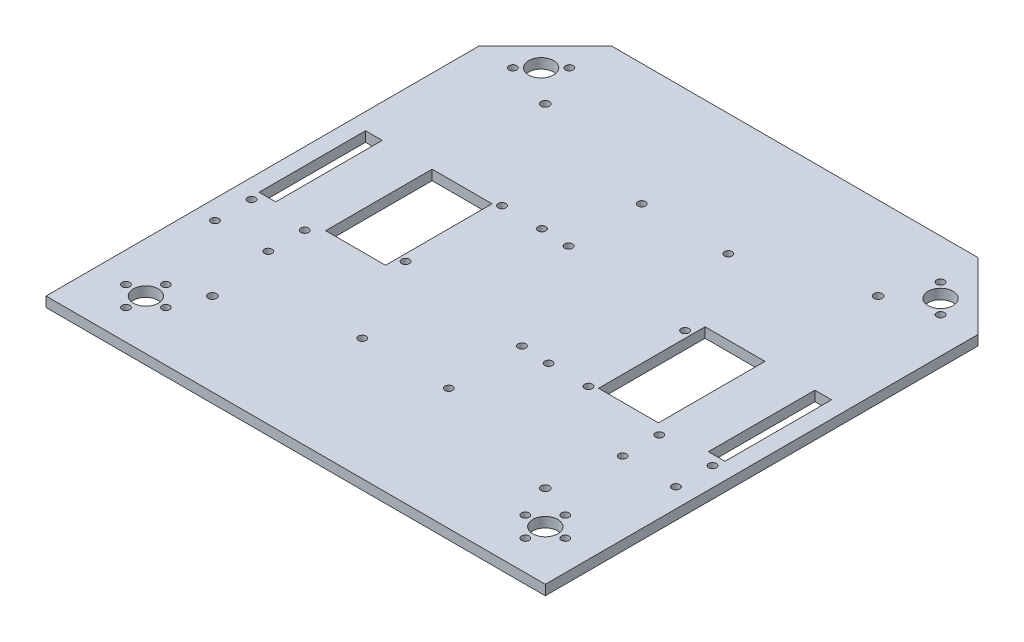
SolidWorks part; units mm, degrees
ref_plane "Plan de face" through (0, 0, 0) normal (0, 0, 1) x (1, 0, 0)
ref_plane "Plan de dessus" through (0, 0, 0) normal (0, 1, 0) x (1, 0, 0)
ref_plane "Plan de droite" through (0, 0, 0) normal (1, 0, 0) x (0, 0, -1)
sketch "Esquisse1" plane through (0, 0, 0) normal (0, 1, 0) x (1, 0, 0)
  line L0 (-150, 0) -> (-150, 260)
  line L2 (150, 0) -> (150, 260)
  line L3 (-150, 260) -> (-110, 260) construction
  line L4 (-110, 260) -> (-110, 300) construction
  line L5 (150, 260) -> (110, 260) construction
  line L6 (110, 260) -> (110, 300) construction
  line L8 (-150, 260) -> (-110, 300)
  line L9 (-110, 300) -> (110, 300)
  line L10 (0, 0) -> (0, 300) construction
  line L11 (110, 300) -> (150, 260)
  line L12 (-150, 0) -> (-120, 0) construction
  line L13 (-120, 18) -> (-120, 0) construction
  line L14 (150, 0) -> (120, 0) construction
  line L15 (120, 18) -> (120, 0) construction
  line L17 (-150, 260) -> (-120, 260) construction
  line L18 (-120, 260) -> (-120, 267.5) construction
  line L19 (150, 260) -> (120, 260) construction
  line L20 (120, 260) -> (120, 267.5) construction
  line L21 (-120, 267.5) -> (-111.5147, 275.9853) construction
  line L22 (-120, 267.5) -> (-128.4853, 259.0147) construction
  line L23 (120, 267.5) -> (128.4853, 259.0147) construction
  line L24 (120, 267.5) -> (111.5147, 275.9853) construction
  line L25 (-150, 0) -> (150, 0) construction
  line L26 (120, 30) -> (120, 18) construction
  line L27 (120, 30) -> (120, 42) construction
  line L28 (-150, 0) -> (150, 0)
  line L29 (-120, 18) -> (-120, 30) construction
  line L30 (-120, 30) -> (-120, 42) construction
  line L32 (150, 150) -> (-150, 150) construction
  line L33 (-120, 30) -> (-108, 30) construction
  line L34 (-120, 30) -> (-132, 30) construction
  line L35 (120, 30) -> (132, 30) construction
  line L36 (120, 30) -> (108, 30) construction
  circle A2 centre (-120, 30) radius 7.5
  circle A4 centre (-120, 267.5) radius 7.5
  circle A5 centre (120, 267.5) radius 7.5
  circle A6 centre (-111.5147, 275.9853) radius 2.3
  circle A7 centre (-128.4853, 259.0147) radius 2.3
  circle A8 centre (111.5147, 275.9853) radius 2.3
  circle A9 centre (128.4853, 259.0147) radius 2.3
  circle A10 centre (120, 30) radius 7.5
  circle A11 centre (120, 42) radius 2.3
  circle A13 centre (-120, 42) radius 2.3
  circle A14 centre (-120, 18) radius 2.3
  circle A16 centre (-132, 30) radius 2.3
  circle A17 centre (-108, 30) radius 2.3
  circle A18 centre (108, 30) radius 2.3
  circle A19 centre (132, 30) radius 2.3
  circle A20 centre (120, 18) radius 2.3
extrude "Boss.-Extru.1" add sketch "Esquisse1" along normal blind 6
sketch "Esquisse7" plane through (0, 6, 0) normal (0, 1, 0) x (1, 0, 0)
  line L0 (0, 150) -> (-130, 150) construction
  line L1 (0, 0) -> (0, 300) construction
  line L2 (150, 150) -> (-150, 150) construction
  line L3 (-130, 150) -> (-130, 182)
  line L4 (-130, 182) -> (-140, 182)
  line L5 (-140, 182) -> (-140, 118)
  line L6 (-140, 118) -> (-130, 118)
  line L7 (-130, 118) -> (-130, 150)
extrude "Enlèv. mat.-Extru.9" cut sketch "Esquisse7" against normal blind 10.5
sketch "Esquisse6" plane through (0, 6, 0) normal (0, 1, 0) x (1, 0, 0)
  line L0 (-142.5, 116) -> (-134.5, 116) construction
  line L2 (-142.5, 116) -> (-142.5, 150) construction
  line L3 (-142.5, 116) -> (-142.5, 108) construction
  line L11 (-142.5, 108) -> (-134.5, 108) construction
  line L12 (-134.5, 108) -> (-134.5, 116) construction
  line L14 (-142.5, 150) -> (-150, 150) construction
  line L15 (-142.5, 116) -> (-102.5, 116) construction
  line L16 (-102.5, 116) -> (-102.5, 108) construction
  line L17 (-102.5, 108) -> (-110.5, 108) construction
  line L18 (-110.5, 108) -> (-110.5, 116) construction
  line L19 (-110.5, 116) -> (-134.5, 116) construction
  line L20 (-134.5, 116) -> (-134.5, 86) construction
  line L21 (-134.5, 86) -> (-142.5, 86) construction
  line L22 (-142.5, 86) -> (-142.5, 94) construction
  line L23 (-142.5, 94) -> (-134.5, 94) construction
  line L24 (-134.5, 94) -> (-134.5, 86) construction
  line L25 (-134.5, 86) -> (-110.5, 86) construction
  line L26 (-110.5, 86) -> (-110.5, 94) construction
  line L27 (-110.5, 94) -> (-102.5, 94) construction
  line L28 (-102.5, 94) -> (-102.5, 86) construction
  line L29 (-102.5, 86) -> (-110.5, 86) construction
  line L30 (-102.5, 94) -> (-110.5, 86) construction
  line L31 (-110.5, 94) -> (-102.5, 86) construction
  line L32 (-142.5, 94) -> (-134.5, 86) construction
  line L33 (-142.5, 86) -> (-134.5, 94) construction
  line L34 (-142.5, 116) -> (-134.5, 108) construction
  line L35 (-142.5, 108) -> (-134.5, 116) construction
  line L71 (-110.5, 116) -> (-102.5, 108) construction
  line L72 (-110.5, 108) -> (-102.5, 116) construction
  line L73 (-110.5, 116) -> (-110.5, 86) construction
  circle A20 centre (-138.5, 90) radius 2.3
  circle A21 centre (-138.5, 112) radius 2.3
  circle A22 centre (-106.5, 112) radius 2.3
  circle A23 centre (-106.5, 90) radius 2.3
  dimension "D1" = 7.5
  dimension "D2" = 34
sketch "Esquisse4" plane through (0, 6, 0) normal (0, 1, 0) x (1, 0, 0)
  line L0 (-150, 150) -> (-100, 150) construction
  line L8 (150, 150) -> (-150, 150) construction
  line L14 (-100, 150) -> (-100, 182)
  line L15 (-100, 250) -> (-100, 50) construction
  line L16 (-100, 150) -> (-100, 118)
  line L17 (-100, 118) -> (-64, 118)
  line L18 (-64, 118) -> (-64, 182)
  line L19 (-64, 182) -> (-100, 182)
sketch "Esquisse9" plane through (0, 6, 0) normal (0, 1, 0) x (1, 0, 0)
  line L0 (-150, 0) -> (150, 0) construction
  line L1 (150, 0) -> (150, 300) construction
  line L2 (150, 300) -> (-150, 300) construction
  line L3 (-150, 300) -> (-150, 0) construction
  line L5 (-150, 0) -> (-150, 300) construction
  line L6 (150, 0) -> (0, 0) construction
  line L7 (0, 0) -> (0, 50) construction
  line L8 (0, 0) -> (0, 300) construction
  line L9 (0, 50) -> (100, 50) construction
  line L10 (100, 50) -> (100, 250) construction
  line L11 (100, 250) -> (-100, 250) construction
  line L12 (-100, 250) -> (-100, 50) construction
  line L13 (-100, 50) -> (0, 50) construction
  line L18 (100, 250) -> (94.3431, 244.3431) construction
  line L21 (-150, 0) -> (150, 300) construction
  circle A0 centre (-100, 50) radius 2.5
  circle A1 centre (100, 50) radius 2.5
  circle A2 centre (100, 250) radius 2.5
  circle A3 centre (-100, 250) radius 2.5
extrude "Enlèv. mat.-Extru.10" cut sketch "Esquisse6" against normal blind 50
extrude "Enlèv. mat.-Extru.11" cut sketch "Esquisse4" against normal blind 50
sketch "Esquisse3" plane through (0, 6, 0) normal (0, 1, 0) x (1, 0, 0)
  line L55 (150, 150) -> (65, 150) construction
  line L56 (150, 150) -> (-150, 150) construction
mirror "Symétrie1" about plane through (0, 0, 0) normal (1, 0, 0) of "Enlèv. mat.-Extru.9"
mirror "Symétrie2" about plane through (0, 0, 0) normal (1, 0, 0) of "Enlèv. mat.-Extru.11"
mirror "Symétrie3" about plane through (0, 0, 0) normal (1, 0, 0) of "Enlèv. mat.-Extru.10"
extrude "Enlèv. mat.-Extru.12" cut sketch "Esquisse9" against normal blind 35
sketch "Esquisse11" plane through (0, 6, 0) normal (0, 1, 0) x (1, 0, 0)
  line L0 (-64, 150) -> (-64, 130) construction
  line L2 (-64, 118) -> (-64, 182) construction
  line L3 (32, 223) -> (-23, 223) construction
  line L4 (-23, 223) -> (-23, 187) construction
  line L5 (-23, 187) -> (-15, 187) construction
  line L6 (-15, 187) -> (-15, 179) construction
  line L7 (-64, 150) -> (-64, 180) construction
  line L8 (-64, 180) -> (-32, 180) construction
  line L9 (-32, 180) -> (-32, 77) construction
  line L10 (-64, 130) -> (-56, 130) construction
  line L11 (-56, 130) -> (-56, 122) construction
  line L12 (-56, 122) -> (-64, 130) construction
  line L13 (-64, 130) -> (-56, 130) construction
  line L14 (-56, 130) -> (-64, 122) construction
  line L15 (-64, 122) -> (-56, 122) construction
  line L16 (-64, 180) -> (-64, 188) construction
  line L17 (-64, 188) -> (-56, 188) construction
  line L18 (-56, 188) -> (-56, 180) construction
  line L19 (-56, 180) -> (-64, 188) construction
  line L20 (-64, 188) -> (-56, 188) construction
  line L21 (64, 150) -> (64, 170) construction
  line L22 (64, 170) -> (56, 170) construction
  line L23 (56, 170) -> (56, 178) construction
  line L24 (56, 178) -> (64, 178) construction
  line L25 (64, 178) -> (64, 170) construction
  line L26 (64, 170) -> (56, 178) construction
  line L27 (56, 178) -> (56, 170) construction
  line L28 (56, 170) -> (64, 178) construction
  line L29 (64, 150) -> (64, 120) construction
  line L30 (64, 118) -> (64, 182) construction
  line L31 (64, 120) -> (32, 120) construction
  line L32 (32, 120) -> (32, 165) construction
  line L33 (32, 165) -> (37, 165) construction
  line L34 (37, 165) -> (37, 129.3158) construction
  line L35 (37, 129.3158) -> (64, 129.3158) construction
  line L36 (32, 120) -> (32, 223) construction
  line L37 (-15, 179) -> (-23, 179) construction
  line L38 (-23, 179) -> (-23, 187) construction
  line L39 (-23, 187) -> (-15, 179) construction
  line L40 (-15, 179) -> (-15, 187) construction
  line L41 (-15, 187) -> (-23, 179) construction
  line L42 (32, 223) -> (37, 223) construction
  line L43 (37, 223) -> (37, 231) construction
  line L44 (37, 231) -> (29, 231) construction
  line L45 (-23, 223) -> (-23, 231) construction
  line L46 (-23, 231) -> (-15, 231) construction
  line L47 (64, 120) -> (64, 112) construction
  line L48 (64, 112) -> (56, 112) construction
  line L49 (56, 112) -> (56, 120) construction
  line L50 (56, 120) -> (64, 112) construction
  line L51 (64, 112) -> (64, 120) construction
  line L52 (64, 120) -> (56, 112) construction
  line L53 (56, 112) -> (56, 120) construction
  line L54 (56, 120) -> (32, 120) construction
  line L55 (32, 120) -> (32, 112) construction
  line L56 (32, 112) -> (40, 112) construction
  line L57 (40, 112) -> (40, 120) construction
  line L58 (40, 120) -> (32, 112) construction
  line L59 (32, 112) -> (32, 120) construction
  line L60 (32, 120) -> (40, 112) construction
  line L61 (-15, 231) -> (-15, 223) construction
  line L62 (-15, 223) -> (-23, 231) construction
  line L63 (-23, 231) -> (-23, 223) construction
  line L64 (-23, 223) -> (-15, 231) construction
  line L65 (29, 231) -> (29, 223) construction
  line L66 (29, 223) -> (37, 231) construction
  line L67 (37, 231) -> (29, 231) construction
  line L68 (29, 231) -> (37, 223) construction
  line L69 (-56, 188) -> (-64, 180) construction
  line L70 (-64, 180) -> (-32, 180) construction
  line L71 (-32, 180) -> (-32, 188) construction
  line L72 (-32, 188) -> (-40, 188) construction
  line L73 (-40, 188) -> (-40, 180) construction
  line L74 (-40, 180) -> (-32, 188) construction
  line L75 (-32, 188) -> (-40, 188) construction
  line L76 (-40, 188) -> (-32, 180) construction
  line L77 (-32, 180) -> (-32, 77) construction
  line L78 (-32, 77) -> (-37, 77) construction
  line L79 (-37, 77) -> (-37, 69) construction
  line L80 (-37, 69) -> (-29, 69) construction
  line L81 (-29, 69) -> (-29, 77) construction
  line L82 (-29, 77) -> (-37, 69) construction
  line L83 (-37, 69) -> (-37, 77) construction
  line L84 (-37, 77) -> (-29, 69) construction
  line L85 (-29, 69) -> (-29, 77) construction
  line L86 (-29, 77) -> (-37, 77) construction
  line L87 (-37, 77) -> (23, 77) construction
  line L88 (23, 77) -> (23, 69) construction
  line L89 (23, 69) -> (15, 69) construction
  line L90 (15, 69) -> (15, 77) construction
  line L91 (15, 77) -> (23, 69) construction
  line L92 (23, 69) -> (23, 77) construction
  line L93 (23, 77) -> (15, 69) construction
  line L94 (15, 69) -> (23, 69) construction
  line L95 (23, 69) -> (23, 77) construction
  line L96 (23, 77) -> (23, 113) construction
  line L97 (23, 113) -> (-32, 113) construction
  line L98 (23, 113) -> (23, 121) construction
  line L99 (23, 121) -> (15, 121) construction
  line L100 (15, 121) -> (15, 113) construction
  line L101 (15, 113) -> (23, 121) construction
  line L102 (23, 121) -> (15, 121) construction
  line L103 (15, 121) -> (23, 113) construction
  circle A4 centre (36, 116) radius 2.3
  circle A5 centre (60, 116) radius 2.3
  circle A7 centre (60, 174) radius 2.3
  circle A8 centre (-19, 227) radius 2.3
  circle A12 centre (-19, 183) radius 2.3
  circle A13 centre (33, 227) radius 2.3
  circle A14 centre (19, 117) radius 2.3
  circle A15 centre (19, 73) radius 2.3
  circle A17 centre (-33, 73) radius 2.3
  circle A18 centre (-60, 126) radius 2.3
  circle A19 centre (-36, 184) radius 2.3
  circle A20 centre (-60, 184) radius 2.3
  dimension "D1" = 50
  dimension "D2" = 32
  dimension "D3" = 20
extrude "Enlèv. mat.-Extru.15" cut sketch "Esquisse11" against normal blind 10
